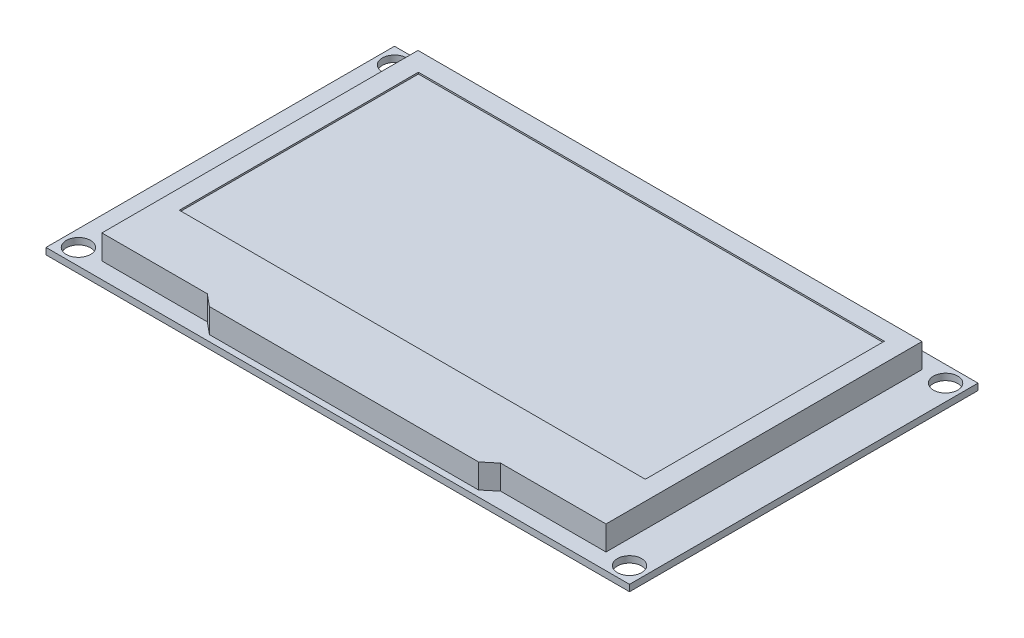
SolidWorks part; units mm, degrees
ref_plane "Plan de face" through (0, 0, 0) normal (0, 0, 1) x (1, 0, 0)
ref_plane "Plan de dessus" through (0, 0, 0) normal (0, 1, 0) x (1, 0, 0)
ref_plane "Plan de droite" through (0, 0, 0) normal (1, 0, 0) x (0, 0, -1)
sketch "Sketch1" plane through (0, 0, 0) normal (0, 1, 0) x (1, 0, 0)
  line L0 (-70, 43) -> (-70, 0) construction
  line L1 (0, 0) -> (-72, 0)
  line L2 (0, 0) -> (0, 43)
  line L3 (0, 43) -> (-72, 43)
  line L4 (-72, 0) -> (-72, 43)
  line L5 (-2, 43) -> (-2, 0) construction
  line L6 (-72, 41) -> (0, 41) construction
  line L7 (-72, 2) -> (0, 2) construction
  circle A0 centre (-70, 41) radius 1.5
  circle A1 centre (-2, 41) radius 1.5
  circle A2 centre (-2, 2) radius 1.5
  circle A3 centre (-70, 2) radius 1.5
  dimension "D7" = 3
  dimension "D8" = 3
  dimension "D9" = 3
  dimension "D10" = 3
  dimension "D1" = 72
  dimension "D2" = 43
  dimension "D3" = 2
  dimension "D4" = 2
  dimension "D5" = 2
  dimension "D6" = 2
extrude "Boss-Extrude1" add sketch "Sketch1" along normal blind 0.8
sketch "Sketch2" plane through (0, 0.8, 0) normal (0, 1, 0) x (1, 0, 0)
  line L0 (0, 43) -> (-72, 43) construction
  line L1 (-67.1, 41) -> (-4.9, 41)
  line L2 (-67.1, 41) -> (-67.1, 2)
  line L3 (-67.1, 2) -> (-4.9, 2)
  line L4 (-4.9, 41) -> (-4.9, 2)
  line L7 (0, 0) -> (0, 43) construction
  line L11 (-19.4, 0.7627) -> (-17.9, 2)
  line L12 (-52.6, 2) -> (-19.4, 2)
  line L13 (-52.6, 2) -> (-52.6, 0.7627)
  line L14 (-52.6, 0.7627) -> (-19.4, 0.7627)
  line L15 (-19.4, 2) -> (-19.4, 0.7627)
  line L16 (-52.6, 0.7627) -> (-54.1, 2)
  dimension "D1" = 62.2
  dimension "D2" = 39
  dimension "D3" = 2
  dimension "D4" = 4.9
  dimension "D5" = 14.5
  dimension "D6" = 14.5
  dimension "D7" = 13
  dimension "D8" = 13
extrude "Boss-Extrude2" add sketch "Sketch2" along normal blind 3 contours L4 L1 L2 L3 | L15 L3 L13 L14 | L3 L15 L11 | L16 L13 L3
sketch "Sketch3" plane through (0, 3.8, 0) normal (0, 1, 0) x (1, 0, 0)
  line L0 (-4.9, 41) -> (-4.9, 2) construction
  line L1 (-64.75, 38.7) -> (-7.25, 38.7)
  line L2 (-64.75, 38.7) -> (-64.75, 9.2)
  line L3 (-64.75, 9.2) -> (-7.25, 9.2)
  line L4 (-7.25, 38.7) -> (-7.25, 9.2)
  line L7 (-67.1, 41) -> (-4.9, 41) construction
  dimension "D1" = 29.5
  dimension "D2" = 57.5
  dimension "D3" = 2.35
  dimension "D4" = 2.3
extrude "Cut-Extrude1" cut sketch "Sketch3" against normal blind 0.2
sketch "Sketch4" plane through (0, 0, 0) normal (0, -1, 0) x (1, 0, 0)
  line L0 (-72, 0) -> (0, 0) construction
  line L1 (-71, -12.75) -> (-68.5, -12.75)
  line L2 (-71, -12.75) -> (-71, -30.25)
  line L3 (-71, -30.25) -> (-68.5, -30.25)
  line L4 (-68.5, -12.75) -> (-68.5, -30.25)
  line L7 (-72, -43) -> (-72, 0) construction
  dimension "D1" = 2.5
  dimension "D2" = 17.5
  dimension "D3" = 12.75
  dimension "D4" = 3.5
extrude "Boss-Extrude3" add sketch "Sketch4" along normal blind 2.5
sketch "Sketch5" plane through (0, -2.5, 0) normal (0, -1, 0) x (1, 0, 0)
  line L0 (-71, -12.75) -> (-71, -30.25) construction
  line L1 (-70, -13.75) -> (-69.5, -13.75)
  line L2 (-70, -13.75) -> (-70, -14.25)
  line L3 (-70, -14.25) -> (-69.5, -14.25)
  line L4 (-69.5, -13.75) -> (-69.5, -14.25)
  line L5 (-68.5, -12.75) -> (-71, -12.75) construction
  dimension "D1" = 0.5
  dimension "D2" = 0.5
  dimension "D3" = 1
  dimension "D4" = 1
extrude "Boss-Extrude4" add sketch "Sketch5" along normal blind 6
pattern_linear "LPattern1" count 7 spacing 2.5 along (0, 0, -1) of "Boss-Extrude4"
